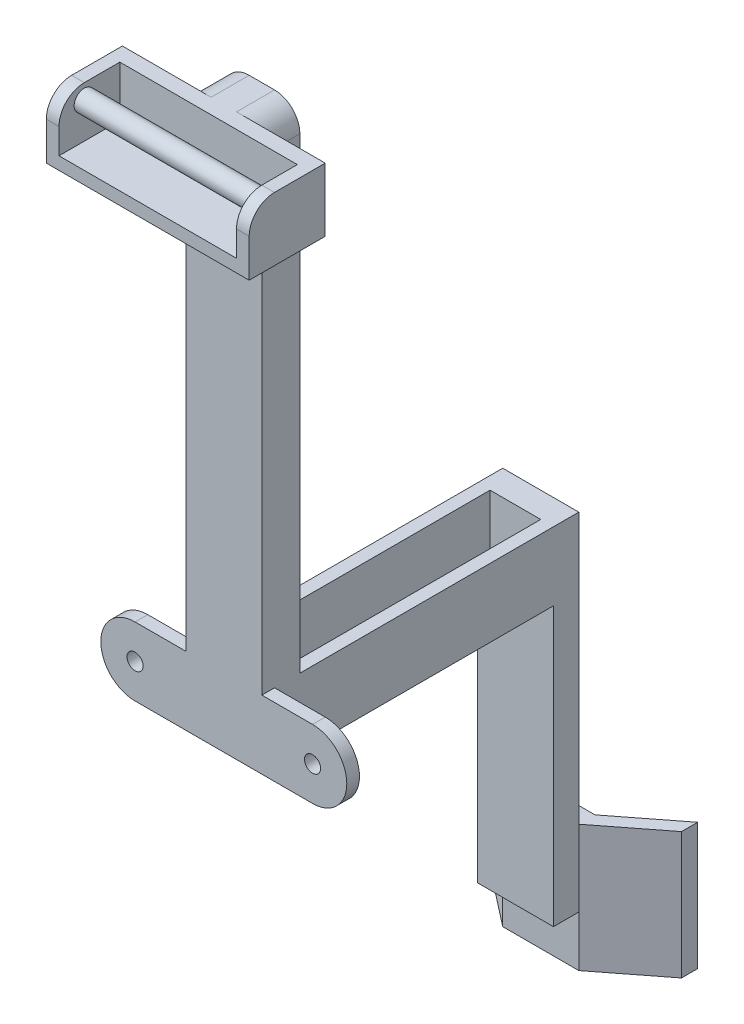
SolidWorks part; units mm, degrees
ref_plane "Front Plane" through (0, 0, 0) normal (0, 0, 1) x (1, 0, 0)
ref_plane "Top Plane" through (0, 0, 0) normal (0, 1, 0) x (1, 0, 0)
ref_plane "Right Plane" through (0, 0, 0) normal (1, 0, 0) x (0, 0, -1)
sketch "Sketch1" plane through (0, 0, 0) normal (0, 0, 1) x (1, 0, 0)
  line L0 (50, 212.065) -> (-20, 212.065) construction
  line L1 (30, -62.835) -> (0, -62.835)
  line L2 (30, -62.835) -> (30, 419.765)
  line L3 (30, 419.765) -> (0, 419.765)
  line L4 (0, -62.835) -> (0, 419.765)
  line L5 (30, -62.835) -> (0, 419.765) construction
  line L6 (30, 419.765) -> (0, -62.835) construction
  line L7 (50, 198.565) -> (-20, 198.565)
  line L8 (50, 225.565) -> (-20, 225.565)
  arc A0 (50, 198.565) -> (50, 225.565) centre (50, 212.065) ccw
  arc A1 (-20, 225.565) -> (-20, 198.565) centre (-20, 212.065) ccw
  point P0 (15, 178.465)
  point P7 (15, 212.065)
  dimension "D1" = 482.6
  dimension "D2" = 27
  dimension "D3" = 30
  dimension "D4" = 33.6
  dimension "D5" = 70
  dimension "D6" = 0
extrude "Extrude1" add sketch "Sketch1" along normal blind 15 contours L8 L2 L3 L4 | L7 A0 L8 L2 | L2 L8 L4 L7 | L8 A1 L7 L4 | L2 L7 L4 L1
fillet "Fillet1" radius 10 4 edges at (30, -62.835, 7.5) (0, -62.835, 7.5) (0, 419.765, 7.5) (30, 419.765, 7.5)
sketch "Sketch2" plane through (0, 0, 0) normal (0, 0, -1) x (-1, 0, 0)
  line L0 (-50, 225.565) -> (-30, 225.565) construction
  line L1 (-50, 198.565) -> (-30, 198.565) construction
  line L2 (0, 198.565) -> (20, 198.565) construction
  line L3 (0, 225.565) -> (20, 225.565) construction
  line L4 (-50, 225.565) -> (-30, 225.565)
  line L5 (-50, 198.565) -> (-30, 198.565)
  line L6 (0, 198.565) -> (20, 198.565)
  line L7 (0, 225.565) -> (20, 225.565)
  line L8 (-30, 225.565) -> (-30, 198.565)
  line L9 (0, 225.565) -> (0, 198.565)
  arc A0 (20, 198.565) -> (20, 225.565) centre (20, 212.065) ccw construction
  arc A1 (-50, 225.565) -> (-50, 198.565) centre (-50, 212.065) ccw construction
  arc A2 (20, 198.565) -> (20, 225.565) centre (20, 212.065) ccw
  arc A3 (-50, 225.565) -> (-50, 198.565) centre (-50, 212.065) ccw
extrude "Extrude2" cut sketch "Sketch2" against normal blind 10
sketch "Sketch3" plane through (0, 0, 15) normal (0, 0, 1) x (1, 0, 0)
  line L0 (30, 407.265) -> (0, 407.265) construction
  line L1 (-25, 394.765) -> (55, 394.765)
  line L2 (-25, 394.765) -> (-25, 419.765)
  line L3 (-25, 419.765) -> (55, 419.765)
  line L4 (55, 394.765) -> (55, 419.765)
  line L5 (-25, 394.765) -> (55, 419.765) construction
  line L6 (-25, 419.765) -> (55, 394.765) construction
  line L7 (30, 225.565) -> (30, 409.765) construction
  line L8 (0, 225.565) -> (0, 409.765) construction
  line L9 (15, 407.265) -> (15, 419.765) construction
  line L10 (20, 419.765) -> (10, 419.765) construction
  point P0 (15, 407.265)
  dimension "D1" = 80
  dimension "D2" = 0
  dimension "D3" = 25
  dimension "D4" = 0
extrude "Extrude3" add sketch "Sketch3" along normal blind 30
sketch "Sketch5" plane through (0, 0, 45) normal (0, 0, 1) x (1, 0, 0)
  line L0 (55, 419.765) -> (-25, 419.765) construction
  line L1 (-20, 419.765) -> (50, 419.765)
  line L2 (-20, 419.765) -> (-20, 399.765)
  line L3 (-20, 399.765) -> (50, 399.765)
  line L4 (50, 419.765) -> (50, 399.765)
  line L5 (-25, 419.765) -> (-25, 394.765) construction
  line L6 (55, 394.765) -> (55, 419.765) construction
  line L7 (-25, 394.765) -> (55, 394.765) construction
  dimension "D1" = 5
  dimension "D2" = 5
  dimension "D3" = 5
extrude "Extrude4" cut sketch "Sketch5" against normal blind 24
fillet "Fillet2" radius 10 2 edges at (-22.5, 419.765, 45) (52.5, 419.765, 45)
sketch "Sketch6" plane through (50, 0, 0) normal (-1, 0, 0) x (0, 0, 1)
  circle A0 centre (35, 413.8477) radius 4.0292
extrude "Extrude5" add sketch "Sketch6" along normal up to next
sketch "Sketch7" plane through (0, 0, 0) normal (0, 0, -1) x (-1, 0, 0)
  line L0 (0, 198.565) -> (-30, 198.565)
  line L1 (-30, 198.565) -> (-30, -64.8073)
  line L2 (-30, -64.8073) -> (0, -64.8073)
  line L3 (0, -64.8073) -> (0, 198.565)
extrude "Extrude6" cut sketch "Sketch7" against normal through all
sketch "Sketch8" plane through (0, 0, 0) normal (0, 0, -1) x (-1, 0, 0)
  line L0 (-30, 198.565) -> (0, 198.565)
  line L1 (0, 198.565) -> (0, 225.565)
  line L2 (0, 225.565) -> (-5, 225.565)
  line L3 (-5, 225.565) -> (-5, 203.565)
  line L4 (-5, 203.565) -> (-25, 203.565)
  line L5 (-25, 203.565) -> (-25, 225.565)
  line L6 (-25, 225.565) -> (-30, 225.565)
  line L7 (-30, 198.565) -> (-30, 225.565) construction
  line L8 (-30, 198.565) -> (-30, 409.765) construction
  line L9 (-30, 225.565) -> (-30, 198.565)
  dimension "D1" = 5
  dimension "D2" = 5
  dimension "D3" = 5
extrude "Extrude7" add sketch "Sketch8" along normal blind 100
sketch "Sketch9" plane through (0, 0, -100) normal (0, 0, -1) x (-1, 0, 0)
  line L1 (-30, 225.565) -> (0, 225.565)
  line L2 (-30, 225.565) -> (-30, 88.9838)
  line L3 (-30, 88.9838) -> (0, 88.9838)
  line L4 (0, 225.565) -> (0, 88.9838)
extrude "Extrude8" add sketch "Sketch9" along normal blind 10
hole_wizard "1/4 (0.25) Diameter Hole1" positions "3DSketch1" profile "Sketch10" hole size "1/4" standard "Ansi Inch"
sketch3d "3DSketch1"
  line L0 (-20, 212.065, 15) -> (-20, 212.065, 10) construction
  line L1 (50, 212.065, 15) -> (50, 212.065, 10) construction
  point P0 (-20, 212.065, 10)
  point P4 (50, 212.065, 10)
sketch "Sketch10" plane through (-20, 212.065, 10) normal (1, 0, 0) x (0, 1, 0)
  line L0 (0, 0) -> (0, 11.9077)
  line L1 (0, 11.9077) -> (3.175, 10)
  line L2 (3.175, 10) -> (3.175, 0)
  line L5 (3.175, 0) -> (0, 0)
  line L10 (0, 11.9077) -> (-3.175, 10) construction
  line L11 (0, -6.35) -> (0, 107.95) construction
  dimension "Hole Dia." = 6.35
  dimension "Hole Depth" = 10
  dimension "Drill Angle" = 118
sketch "Sketch11" plane through (0, 88.9838, 0) normal (0, -1, 0) x (1, 0, 0)
  line L0 (30, -116.3786) -> (30, -110)
  line L1 (0, -110) -> (30, -110)
  line L2 (0, -110) -> (0, -116.3786)
  line L3 (0, -116.3786) -> (30, -116.3786)
  line L4 (30, -110) -> (30, -116.3786)
  line L5 (30, -116.3786) -> (52.7841, -134.1027)
  line L6 (30, -110) -> (52.7841, -127.7241)
  line L7 (52.7841, -134.1027) -> (52.7841, -127.7241)
  line L8 (15, -110) -> (15, -116.3786) construction
  line L9 (0, -110) -> (-22.7841, -127.7241)
  line L10 (-22.7841, -134.1027) -> (-22.7841, -127.7241)
  line L11 (0, -116.3786) -> (-22.7841, -134.1027)
  line M3 (0, -110) -> (30, -110)
extrude "Extrude12" add sketch "Sketch11" along normal blind 20 and the other way blind 30 contours L11 L2 L9 L10 | L1 L8 L3 L0 | L8 L2 L3 M3 | L5 L7 L6 L0
